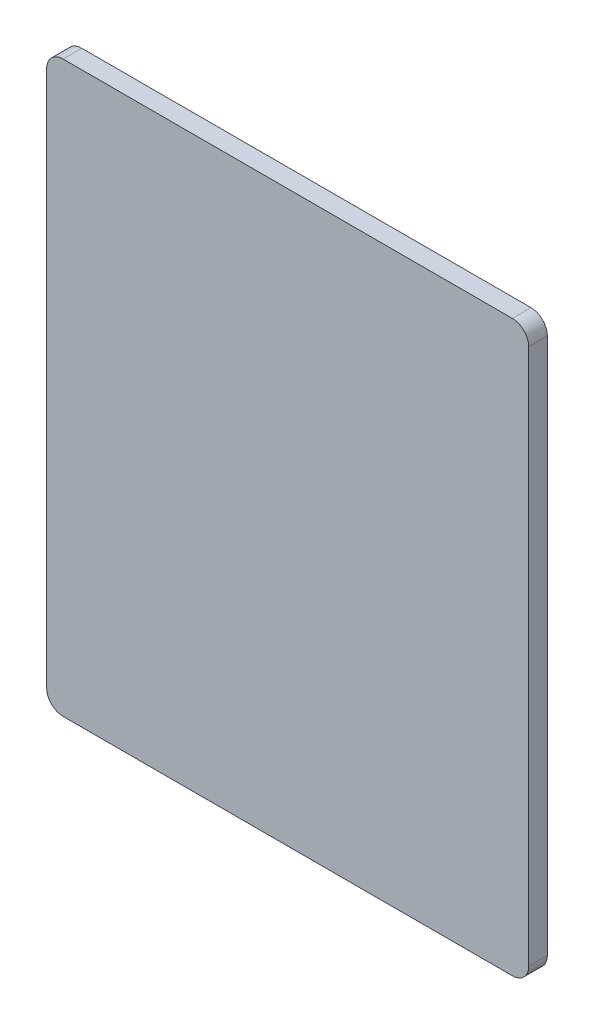
SolidWorks part; units mm, degrees
material "Стекло"
ref_plane "Спереди" through (0, 0, 0) normal (0, 0, 1) x (1, 0, 0)
ref_plane "Сверху" through (0, 0, 0) normal (0, 1, 0) x (1, 0, 0)
ref_plane "Справа" through (0, 0, 0) normal (1, 0, 0) x (0, 0, -1)
other "Configuration Table"
sketch "Эскиз1" plane through (0, 0, 0) normal (0, 0, 1) x (1, 0, 0)
  line L1 (-265, -313) -> (265, -313)
  line L2 (-265, -313) -> (-265, 313)
  line L3 (-265, 313) -> (265, 313)
  line L4 (265, -313) -> (265, 313)
  line L5 (-265, -313) -> (265, 313) construction
  line L6 (-265, 313) -> (265, -313) construction
  point P0 (0, 0)
  dimension "D1" = 530
  dimension "D2" = 626
extrude "Бобышка-Вытянуть1" add sketch "Эскиз1" along normal mid plane 20.5
fillet "Скругление1" radius 18 4 edges at (-265, -313, 0) (265, -313, 0) (265, 313, 0) (-265, 313, 0)
